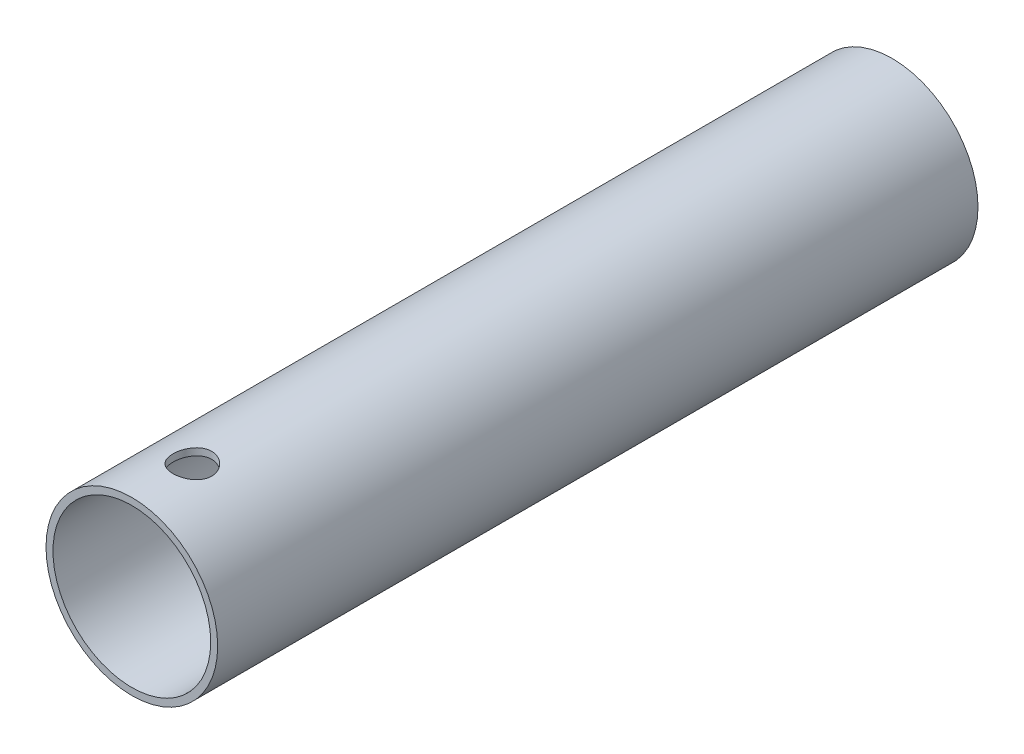
SolidWorks part; units mm, degrees
ref_plane "Front Plane" through (0, 0, 0) normal (0, 0, 1) x (1, 0, 0)
ref_plane "Top Plane" through (0, 0, 0) normal (0, 1, 0) x (1, 0, 0)
ref_plane "Right Plane" through (0, 0, 0) normal (1, 0, 0) x (0, 0, -1)
sketch "Sketch1" plane through (0, 0, 0) normal (0, 0, 1) x (1, 0, 0)
  circle A0 centre (0, 0) radius 254
  circle A1 centre (0, 0) radius 233.4
  dimension "D1" = 508
  dimension "D2" = 20.6
extrude "Boss-Extrude1" add sketch "Sketch1" against normal blind 2250
sketch "Sketch2" plane through (0, 0, 0) normal (0, 1, 0) x (1, 0, 0)
  circle A0 centre (0, 179) radius 57.25
  dimension "D1" = 114.5
  dimension "D2" = 179
extrude "Cut-Extrude1" cut sketch "Sketch2" along normal blind 2250
sketch "Sketch3" plane through (0, 0, 0) normal (0, 1, 0) x (1, 0, 0)
  line L0 (-254, 0) -> (254, 0) construction
  circle A0 centre (0, 2049) radius 57.25
  circle A1 centre (0, 649) radius 24.5
  dimension "D1" = 114.5
  dimension "D2" = 49
  dimension "D3" = 649
  dimension "D4" = 2049
extrude "Cut-Extrude2" cut sketch "Sketch3" against normal blind 2250
